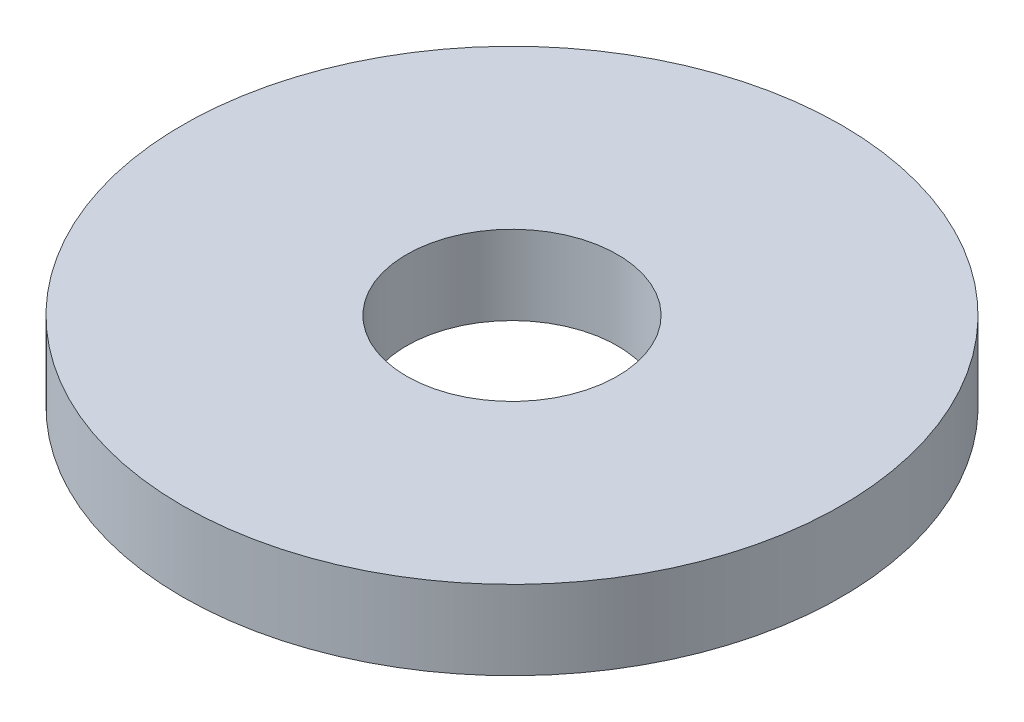
SolidWorks part; units mm, degrees
ref_plane "Front Plane" through (0, 0, 0) normal (0, 0, 1) x (1, 0, 0)
ref_plane "Top Plane" through (0, 0, 0) normal (0, 1, 0) x (1, 0, 0)
ref_plane "Right Plane" through (0, 0, 0) normal (1, 0, 0) x (0, 0, -1)
sketch "Sketch1" plane through (0, 0, 0) normal (0, 1, 0) x (1, 0, 0)
  circle A0 centre (0, 0) radius 12.5
  circle A1 centre (0, 0) radius 4
  dimension "D1" = 12.5
  dimension "D2" = 8
extrude "Boss-Extrude1" add sketch "Sketch1" along normal blind 3
